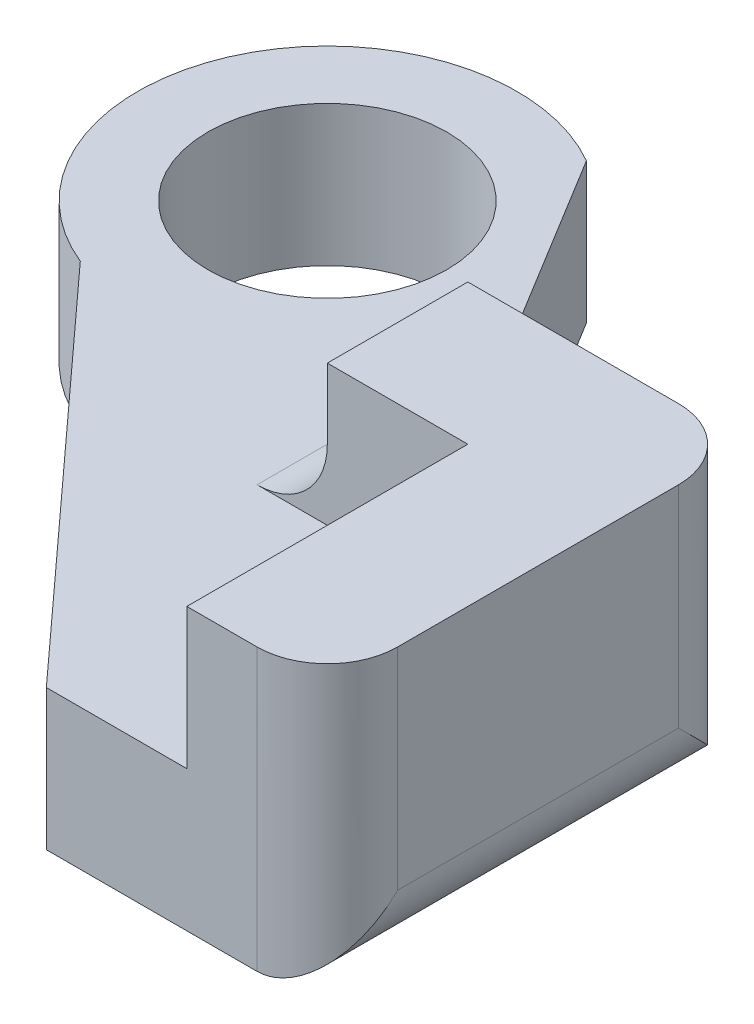
SolidWorks part; units mm, degrees
ref_plane "Front Plane" through (0, 0, 0) normal (0, 0, 1) x (1, 0, 0)
ref_plane "Top Plane" through (0, 0, 0) normal (0, 1, 0) x (1, 0, 0)
ref_plane "Right Plane" through (0, 0, 0) normal (1, 0, 0) x (0, 0, -1)
sketch "Sketch1" plane through (0, 0, 0) normal (0, 1, 0) x (1, 0, 0)
  line L1 (0, 0) -> (20, 0)
  line L2 (0, 0) -> (0, -30)
  line L3 (0, -30) -> (20, -30)
  line L4 (20, 0) -> (20, -30)
  dimension "D1" = 30
  dimension "D2" = 20
extrude "Boss-Extrude1" add sketch "Sketch1" along normal blind 10
sketch "Sketch2" plane through (0, 10, 0) normal (0, 1, 0) x (1, 0, 0)
  line L4 (0, 0) -> (0, -10)
  line L5 (0, -10) -> (10, -10)
  line L6 (10, -10) -> (10, -30)
  line L7 (0, -30) -> (20, -30) construction
  line L8 (10, -30) -> (20, -30)
  line L9 (20, -30) -> (20, 0) construction
  line L10 (20, -30) -> (20, 0)
  line L11 (20, 0) -> (0, 0)
  dimension "D1" = 10
  dimension "D2" = 10
extrude "Boss-Extrude2" add sketch "Sketch2" along normal blind 10
sketch "Sketch4" plane through (0, 10, 0) normal (0, 1, 0) x (1, 0, 0)
  line L0 (0, 0) -> (-13.2471, 21.6896)
  line L1 (0, -30) -> (-25.0721, -2.5109)
  line L2 (0, 0) -> (0, -30)
  line L3 (0, 0) -> (0, -30) construction
  circle A0 centre (-20, 10) radius 8.5
  arc A1 (-13.2471, 21.6896) -> (-25.0721, -2.5109) centre (-20, 10) ccw
  circle A2 centre (-20, 10) radius 13.5 construction
  point P3 (-20, 10)
  dimension "D1" = 17
  dimension "D3" = 20
  dimension "D4" = 10
  dimension "D2" = 5
extrude "Boss-Extrude3" add sketch "Sketch4" against normal up to surface (10 mm away) up to face at (10, 0, 15)
fillet "Fillet1" radius 5 4 edges at (0, 10, 5) (20, 0, 15) (20, 10, 30) (20, 10, 0)
